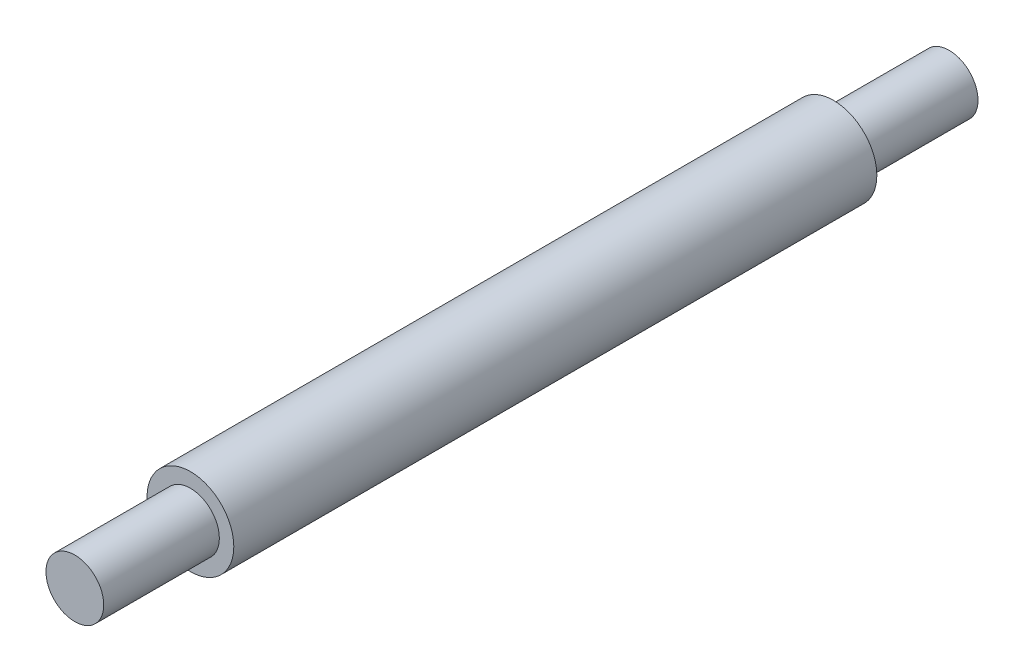
SolidWorks part; units mm, degrees
ref_plane "Front Plane" through (0, 0, 0) normal (0, 0, 1) x (1, 0, 0)
ref_plane "Top Plane" through (0, 0, 0) normal (0, 1, 0) x (1, 0, 0)
ref_plane "Right Plane" through (0, 0, 0) normal (1, 0, 0) x (0, 0, -1)
sketch "Sketch1" plane through (0, 0, 0) normal (0, 0, 1) x (1, 0, 0)
  circle A0 centre (0, 0) radius 3
  dimension "D1" = 6
extrude "Boss-Extrude1" add sketch "Sketch1" along normal blind 44.5
sketch "Sketch2" plane through (0, 0, 44.5) normal (0, 0, 1) x (1, 0, 0)
  circle A0 centre (0, 0) radius 2
  dimension "D1" = 4
extrude "Boss-Extrude2" add sketch "Sketch2" along normal blind 8
sketch "Sketch3" plane through (0, 0, 0) normal (0, 0, -1) x (-1, 0, 0)
  circle A0 centre (0, 0) radius 2
  dimension "D1" = 4
extrude "Boss-Extrude3" add sketch "Sketch3" along normal blind 8
